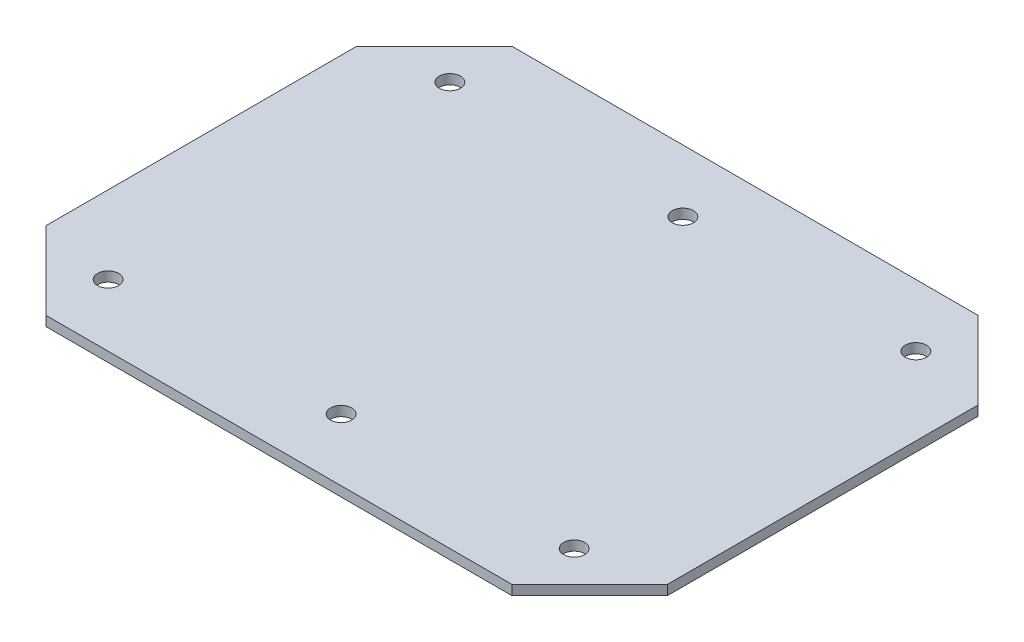
SolidWorks part; units mm, degrees
material "Oshpark board"
ref_plane "Front Plane" through (0, 0, 0) normal (0, 0, 1) x (1, 0, 0)
ref_plane "Top Plane" through (0, 0, 0) normal (0, 1, 0) x (1, 0, 0)
ref_plane "Right Plane" through (0, 0, 0) normal (1, 0, 0) x (0, 0, -1)
sketch "Sketch1" plane through (0, 0, 0) normal (0, 1, 0) x (1, 0, 0)
  line L0 (-50.8, 38.1) -> (50.8, -38.1) construction
  line L1 (-50.8, 38.1) -> (50.8, 38.1)
  line L2 (-50.8, 38.1) -> (-50.8, -38.1)
  line L3 (-50.8, -38.1) -> (50.8, -38.1)
  line L4 (50.8, 38.1) -> (50.8, -38.1)
  dimension "D1" = 76.2
  dimension "D2" = 101.6
extrude "Boss-Extrude1" add sketch "Sketch1" along normal blind 1.6
hole_wizard "#4 Clearance Hole1" positions "Sketch3" profile "Sketch4" hole size "#4" standard "ANSI Inch" end condition through all
sketch "Sketch3" plane through (0, 1.6, 0) normal (0, 1, 0) x (1, 0, 0)
  line L0 (-50.8, 0) -> (50.8, 0) construction
  line L1 (-38.1, -27.94) -> (38.1, -27.94) construction
  line L2 (-50.8, 38.1) -> (-50.8, -38.1) construction
  line L3 (50.8, -38.1) -> (50.8, 38.1) construction
  point P5 (0, 0)
  point P6 (38.1, -27.94)
  point P7 (-38.1, -27.94)
  point P8 (0, -27.94)
  point P9 (38.1, 27.94)
  point P10 (0, 27.94)
  point P11 (-38.1, 27.94)
  dimension "D1" = 76.2
  dimension "D2" = 55.88
sketch "Sketch4" plane through (38.1, 1.6, 27.94) normal (1, 0, 0) x (0, 0, 1)
  line L0 (0, 0) -> (0, 1.6)
  line L1 (0, 1.6) -> (1.7272, 1.6)
  line L2 (1.7272, 1.6) -> (1.7272, 0)
  line L5 (1.7272, 0) -> (0, 0)
  line L11 (0, -6.35) -> (0, 107.95) construction
  dimension "Thru Hole Dia." = 3.4544
  dimension "Thru Hole Depth" = 1.6
chamfer "Chamfer1" distance 12.7 angle 45 4 edges at (50.8, 0.8, 38.1) (50.8, 0.8, -38.1) (-50.8, 0.8, -38.1) (-50.8, 0.8, 38.1)
sketch "Sketch5" plane through (0, 0, 0) normal (0, -1, 0) x (1, 0, 0)
  line L0 (-38.1, 38.1) -> (38.1, 38.1) construction
  line L1 (-28.575, 38.1) -> (-9.525, 38.1)
  line L2 (-28.575, 38.1) -> (-28.575, 25.4)
  line L3 (-28.575, 25.4) -> (-9.525, 25.4)
  line L4 (-9.525, 38.1) -> (-9.525, 25.4)
  line L5 (-38.1, 27.94) -> (-28.575, 27.94) construction
  line L6 (0, 27.94) -> (-9.525, 27.94) construction
  line L7 (0, 38.1) -> (0, -38.1) construction
  line L8 (38.1, -38.1) -> (-38.1, -38.1) construction
  line L10 (-50.8, 0) -> (50.8, 0) construction
  line L11 (-50.8, -25.4) -> (-50.8, 25.4) construction
  line L12 (50.8, 25.4) -> (50.8, -25.4) construction
  line L13 (9.525, 38.1) -> (9.525, 25.4)
  line L14 (28.575, 25.4) -> (9.525, 25.4)
  line L15 (28.575, 38.1) -> (28.575, 25.4)
  line L16 (28.575, 38.1) -> (9.525, 38.1)
  line L17 (28.575, -38.1) -> (9.525, -38.1)
  line L18 (28.575, -38.1) -> (28.575, -25.4)
  line L19 (28.575, -25.4) -> (9.525, -25.4)
  line L20 (9.525, -38.1) -> (9.525, -25.4)
  line L21 (-9.525, -38.1) -> (-9.525, -25.4)
  line L22 (-28.575, -25.4) -> (-9.525, -25.4)
  line L23 (-28.575, -38.1) -> (-28.575, -25.4)
  line L24 (-28.575, -38.1) -> (-9.525, -38.1)
  point P16 (50.8, 0)
  point P17 (-50.8, 0)
  dimension "D1" = 12.7
  dimension "D2" = 19.05
equation "\"boardThickness\"= 1.6mm"
equation "\"D1@Boss-Extrude1\"=\"boardThickness\""
